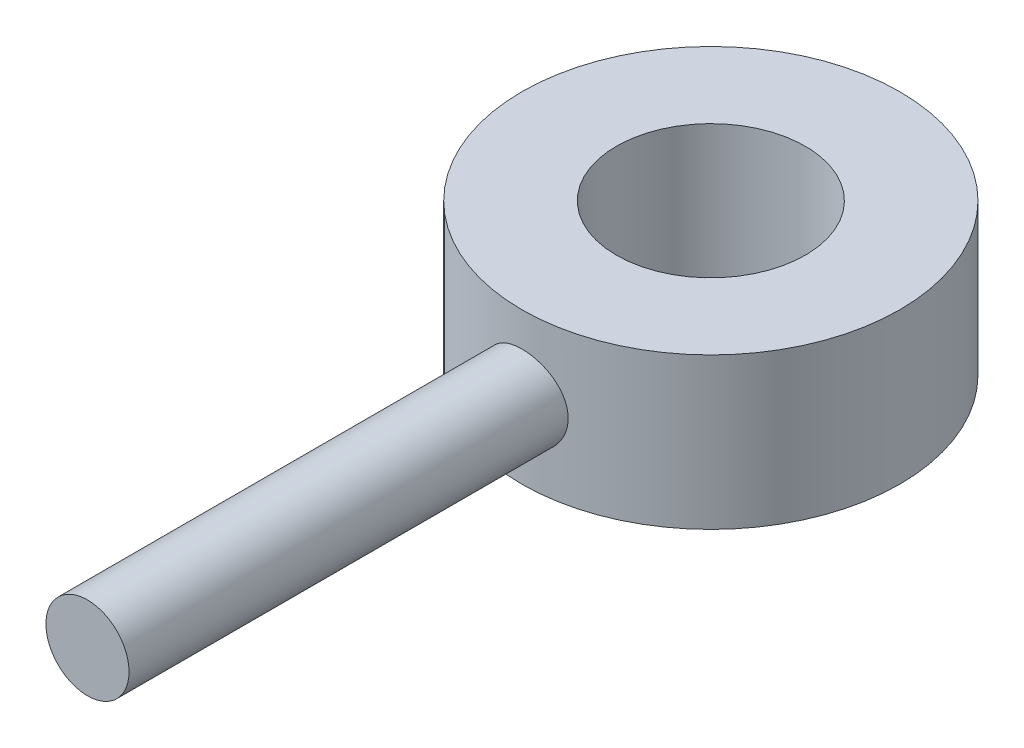
SolidWorks part; units mm, degrees
ref_plane "Front Plane" through (0, 0, 0) normal (0, 0, 1) x (1, 0, 0)
ref_plane "Top Plane" through (0, 0, 0) normal (0, 1, 0) x (1, 0, 0)
ref_plane "Right Plane" through (0, 0, 0) normal (1, 0, 0) x (0, 0, -1)
sketch "Sketch1" plane through (0, 0, 0) normal (0, 1, 0) x (1, 0, 0)
  circle A0 centre (0, 0) radius 5
  circle A1 centre (0, 0) radius 2.5
  dimension "D1" = 10
  dimension "D2" = 5
extrude "Boss-Extrude1" add sketch "Sketch1" along normal blind 4
ref_plane "Plane1" through (0, 0, 16.5) normal (0, 0, 1) x (1, 0, 0)
sketch "Sketch3" plane through (0, 0, 16.5) normal (0, 0, 1) x (1, 0, 0)
  line L0 (5, 4) -> (-5, 4) construction
  circle A0 centre (0, 2) radius 1.1
  dimension "D1" = 2.2
  dimension "D2" = 2
extrude "Boss-Extrude3" add sketch "Sketch3" against normal blind 14
